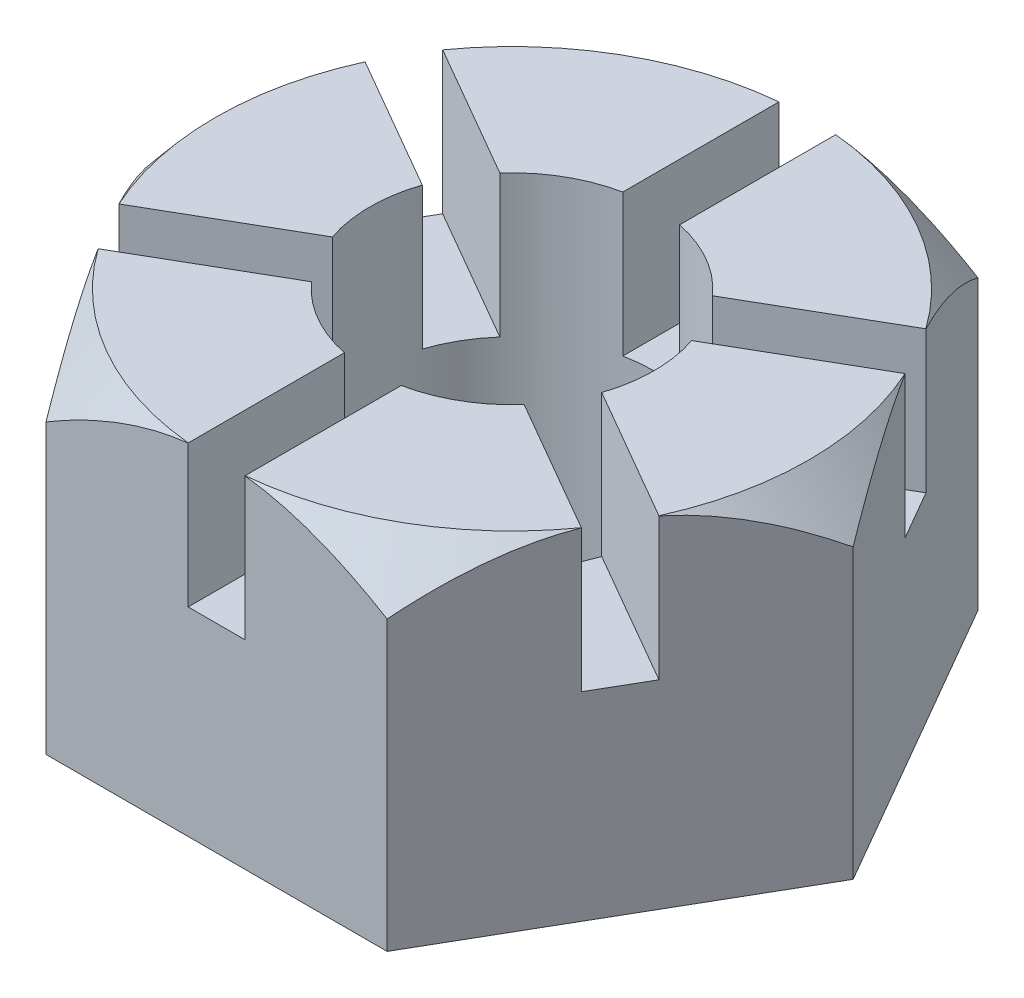
SolidWorks part; units mm, degrees
ref_plane "Front Plane" through (0, 0, 0) normal (0, 0, 1) x (1, 0, 0)
ref_plane "Top Plane" through (0, 0, 0) normal (0, 1, 0) x (1, 0, 0)
ref_plane "Right Plane" through (0, 0, 0) normal (1, 0, 0) x (0, 0, -1)
sketch "Sketch1" plane through (0, 0, 0) normal (0, 1, 0) x (1, 0, 0)
  line L1 (30.0222, -52) -> (60.0444, 0)
  line L2 (60.0444, 0) -> (30.0222, 52)
  line L3 (30.0222, 52) -> (-30.0222, 52)
  line L4 (-30.0222, 52) -> (-60.0444, 0)
  line L5 (-60.0444, 0) -> (-30.0222, -52)
  line L6 (-30.0222, -52) -> (30.0222, -52)
  circle A0 centre (0, 0) radius 52 construction
  dimension "D1" = 104
extrude "Boss-Extrude1" add sketch "Sketch1" along normal blind 60
sketch "Sketch2" plane through (0, 60, 0) normal (0, 1, 0) x (1, 0, 0)
  line L0 (0, 52) -> (0, -53.8344) construction
  line L1 (30.0222, 52) -> (-30.0222, 52) construction
  line L2 (-60.0444, 0) -> (64.2961, 0) construction
  line L3 (-5, 52) -> (-5, 24.4949)
  line L4 (-5, 52) -> (5, 52)
  line L5 (5, 52) -> (5, 24.4949)
  line L6 (42.5333, 30.3301) -> (18.7132, 16.5776)
  line L7 (42.5333, 30.3301) -> (47.5333, 21.6699)
  line L8 (47.5333, 21.6699) -> (23.7132, 7.9173)
  line L9 (47.5333, -21.6699) -> (23.7132, -7.9173)
  line L10 (47.5333, -21.6699) -> (42.5333, -30.3301)
  line L11 (42.5333, -30.3301) -> (18.7132, -16.5776)
  line L12 (5, -52) -> (5, -24.4949)
  line L13 (5, -52) -> (-5, -52)
  line L14 (-5, -52) -> (-5, -24.4949)
  line L15 (-42.5333, -30.3301) -> (-18.7132, -16.5776)
  line L16 (-42.5333, -30.3301) -> (-47.5333, -21.6699)
  line L17 (-47.5333, -21.6699) -> (-23.7132, -7.9173)
  line L18 (-47.5333, 21.6699) -> (-23.7132, 7.9173)
  line L19 (-47.5333, 21.6699) -> (-42.5333, 30.3301)
  line L20 (-42.5333, 30.3301) -> (-18.7132, 16.5776)
  circle A0 centre (0, 0) radius 25
  circle A1 centre (0, 0) radius 25
  circle A2 centre (0, 0) radius 25
  circle A3 centre (0, 0) radius 25
  circle A4 centre (0, 0) radius 25
  circle A5 centre (0, 0) radius 25
  point P42 (0, 0)
  dimension "D1" = 50
  dimension "D2" = 5
  dimension "D3" = 10
  dimension "D4" = 6
extrude "Cut-Extrude9" cut sketch "Sketch2" against normal blind 25 contours A0 L20 L2 L18 | A0 L5 L1 L3 | A0 L8 L4 L6 | A0 L11 L0 L9 | A0 L17 L5 L15 | A0 L14 L3 L12
sketch "Sketch5" plane through (0, 60, 0) normal (0, 1, 0) x (1, 0, 0)
  circle A1 centre (0, 0) radius 52.2248
extrude "Cut-Extrude10" cut sketch "Sketch5" against normal through all draft 40 flip side to cut
sketch "Sketch6" plane through (0, 60, 0) normal (0, 1, 0) x (1, 0, 0)
  circle A0 centre (0, 0) radius 25
  dimension "D1" = 50
extrude "Cut-Extrude11" cut sketch "Sketch6" against normal through all
